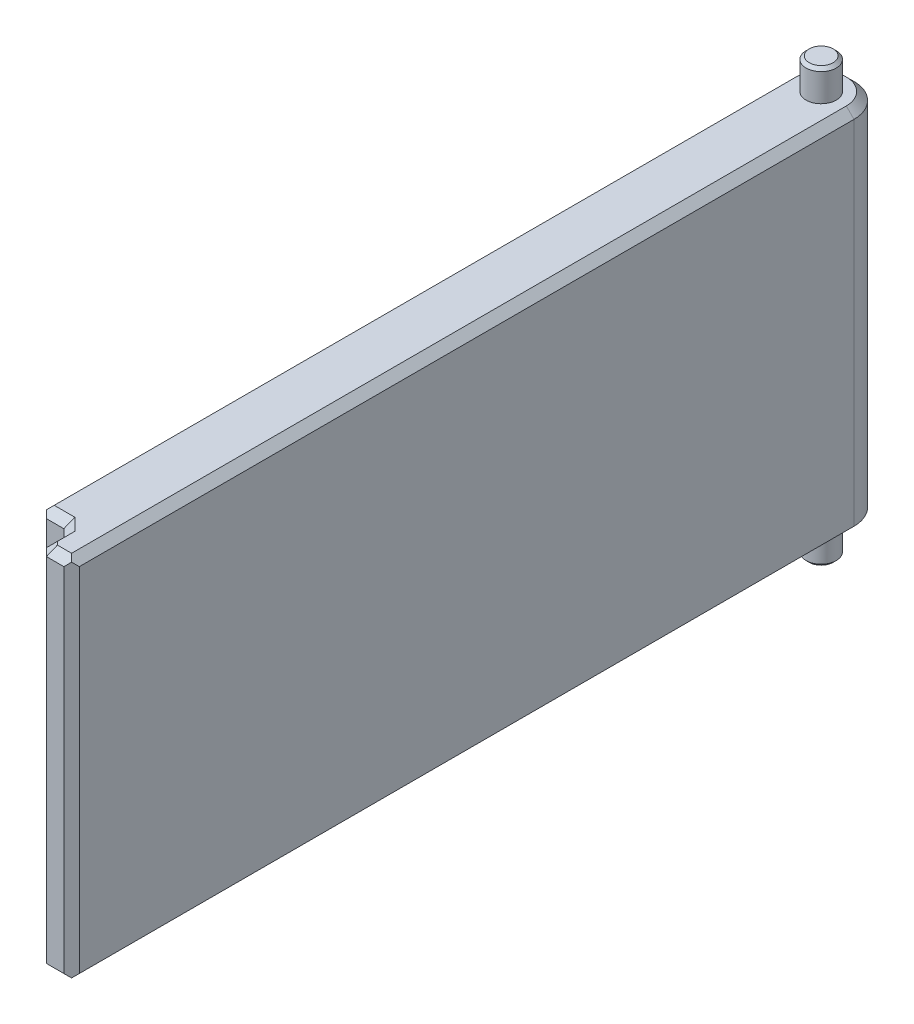
SolidWorks part; units mm, degrees
ref_plane "前视基准面" through (0, 0, 0) normal (0, 0, 1) x (1, 0, 0)
ref_plane "上视基准面" through (0, 0, 0) normal (0, 1, 0) x (1, 0, 0)
ref_plane "右视基准面" through (0, 0, 0) normal (1, 0, 0) x (0, 0, -1)
other "Configuration Table"
sketch "草图2" plane through (0, 0, 0) normal (0, 1, 0) x (1, 0, 0)
  line L0 (0, 0) -> (0, -49.75)
  circle A0 centre (0, 0) radius 0.975
  dimension "D1" = 1.95
extrude "凸台-拉伸1" add sketch "草图2" along normal blind 28
sketch "草图4" plane through (0, 28, 0) normal (0, 1, 0) x (1, 0, 0)
  line L0 (0, -48.5) -> (-2.125, -48.5)
  line L1 (0, -50.625) -> (2.125, -50.625)
  line L2 (0, -50.625) -> (0, -48.5)
  line L3 (-2.125, 0) -> (-2.125, -48.5)
  line L4 (2.125, 0) -> (2.125, -47.7)
  line L6 (2.125, -50.625) -> (2.125, -47.7)
  arc A0 (2.125, 0) -> (-2.125, 0) centre (0, 0) ccw
  point P3 (0, 0)
  point P5 (-13.2697, 1.3286)
  dimension "D1" = 2.125
  dimension "D2" = 48.5
extrude "凸台-拉伸2" add sketch "草图4" against normal blind 23.8
sketch "草图5" plane through (0, 28, 0) normal (0, 1, 0) x (1, 0, 0)
  circle A0 centre (0, 0) radius 0.975
  dimension "D1" = 1.95
extrude "凸台-拉伸3" add sketch "草图5" along normal blind 2
sketch "草图7" plane through (0, 0, 0) normal (0, -1, 0) x (1, 0, 0)
  circle A0 centre (0, 0) radius 2.125
extrude "切除-拉伸1" cut sketch "草图7" against normal blind 2
chamfer "倒角1" distance 0.5 angle 45 6 edges at (-2.125, 28, 24.25) (-2.125, 4.2, 24.25) (0, 28, -2.125) (0, 4.2, -2.125) (2.125, 28, 25.3125) (2.125, 4.2, 25.3125)
chamfer "倒角2" distance 0.5 angle 45 2 edges at (-2.125, 16.1, 48.5) (2.125, 16.1, 50.625)
chamfer "倒角3" distance 0.5 angle 45 2 edges at (0, 16.1, 48.5) (0, 16.1, 50.625)
chamfer "倒角4" distance 0.5 angle 45 10 edges at (-1.0625, 28, 48.5) (-0.25, 28, 48.75) (0, 28, 49.5625) (0, 4.2, 49.5625) (0.25, 28, 50.375) (1.0625, 28, 50.625) (1.0625, 4.2, 50.625) (0.25, 4.2, 50.375) (-0.25, 4.2, 48.75) (-1.0625, 4.2, 48.5)
chamfer "倒角7" distance 0.2 angle 45 2 edges at (0, 30, 0.975) (0, 2, -0.975)
